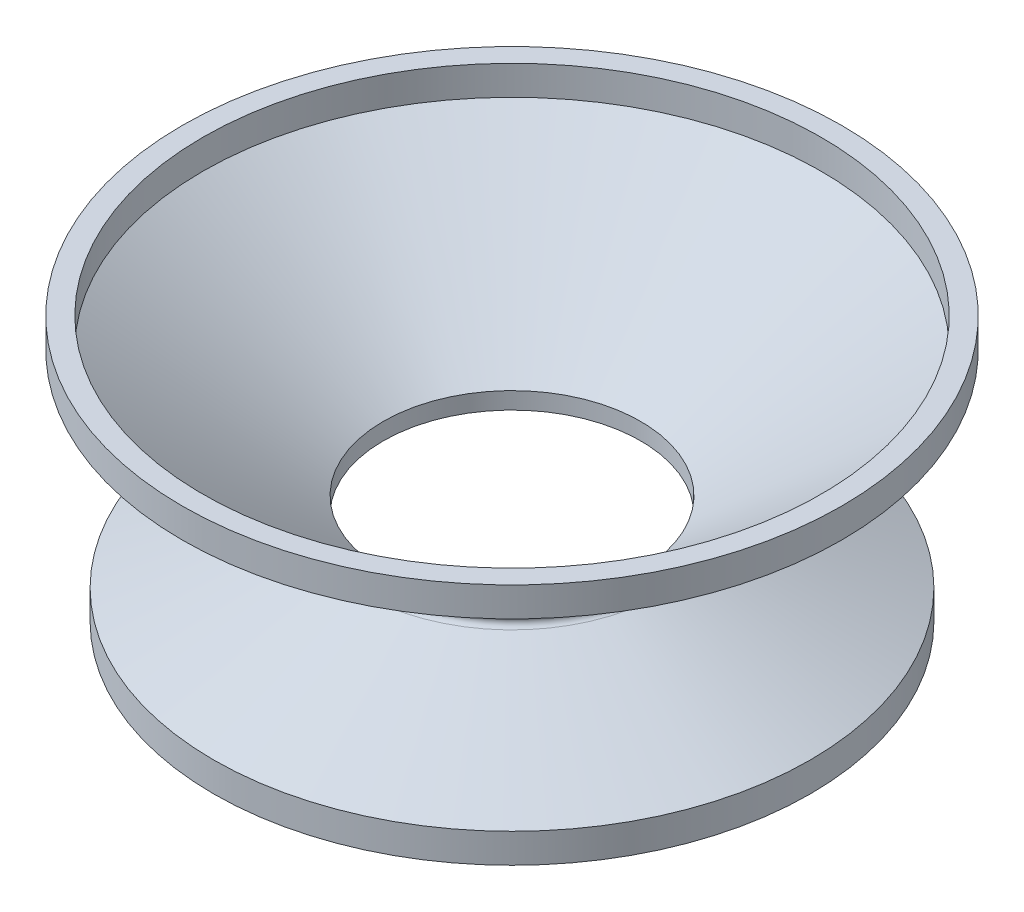
SolidWorks part; units mm, degrees
ref_plane "Front Plane" through (0, 0, 0) normal (0, 0, 1) x (1, 0, 0)
ref_plane "Top Plane" through (0, 0, 0) normal (0, 1, 0) x (1, 0, 0)
ref_plane "Right Plane" through (0, 0, 0) normal (1, 0, 0) x (0, 0, -1)
sketch "Sketch1" plane through (0, 0, 0) normal (0, 0, 1) x (1, 0, 0)
  line L0 (-42.6436, 0) -> (43.9692, 0) construction
  line L1 (0.6628, 0) -> (-12.1906, 9)
  line L2 (0.6628, 0) -> (-10.0598, -5)
  line L3 (1.4628, -0.7303) -> (-7.6936, -5)
  line L5 (-12.1906, 9) -> (-10.7958, 9)
  line L6 (-10.0598, -5) -> (-7.6936, -5)
  line L7 (10.2042, 8.609) -> (10.2042, -6.609) construction
  line L8 (2.6552, -0.1743) -> (-17.679, 14.0639) construction
  line L9 (0.6628, 0) -> (-18.2526, 13.2447) construction
  line L10 (0.6628, 0) -> (-18.8539, -9.1008) construction
  line L11 (2.6552, -0.1743) -> (-18.4313, -10.0071) construction
  line L12 (0.6628, 0) -> (2.2628, 0) construction
  line L13 (1.4628, -0.7303) -> (1.4628, 0.4165)
  line L14 (1.4628, 0.4165) -> (-10.7958, 9)
  point P11 (1.4628, 0)
  dimension "D1" = 35
  dimension "D2" = 25
  dimension "D4" = 9
  dimension "D5" = 5
  dimension "D6" = 21
  dimension "D7" = 1.6
  dimension "D8" = 0.8
  dimension "D3" = 1
revolve "Revolve1" add sketch "Sketch1" angle 360 about L7
scale "Scale1" [suppressed]
fillet "Fillet2" radius 0.4 1 edges at (0.6628, 0, 0)
sketch "Sketch2" plane through (0, 9, 0) normal (0, 1, 0) x (1, 0, 0)
  circle A0 centre (10.2042, 0) radius 22.3948 construction
  circle A1 centre (10.2042, 0) radius 21 construction
  circle A2 centre (10.2042, 0) radius 22.3948
  circle A3 centre (10.2042, 0) radius 21
extrude "Boss-Extrude1" add sketch "Sketch2" along normal blind 2
sketch "Sketch3" plane through (0, -5, 0) normal (0, -1, 0) x (1, 0, 0)
  circle A0 centre (10.2042, 0) radius 17.8978 construction
  circle A1 centre (10.2042, 0) radius 20.264 construction
  circle A2 centre (10.2042, 0) radius 17.8978
  circle A3 centre (10.2042, 0) radius 20.264
extrude "Boss-Extrude2" add sketch "Sketch3" along normal blind 2
